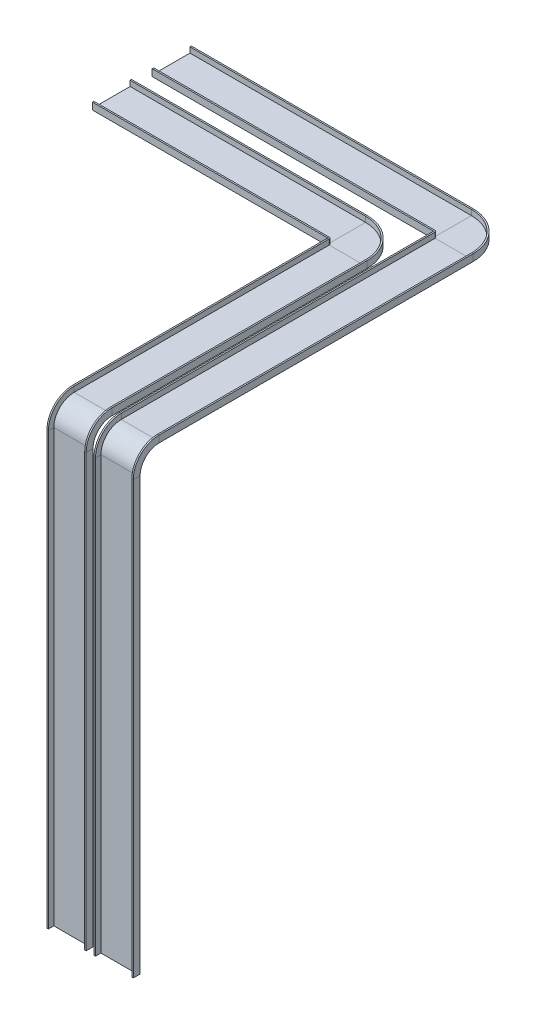
SolidWorks part; units mm, degrees
ref_plane "Alzado" through (0, 0, 0) normal (0, 0, 1) x (1, 0, 0)
ref_plane "Planta" through (0, 0, 0) normal (0, 1, 0) x (1, 0, 0)
ref_plane "Vista lateral" through (0, 0, 0) normal (1, 0, 0) x (0, 0, -1)
sketch "Croquis1" plane through (0, 0, 0) normal (0, 1, 0) x (1, 0, 0)
  line L0 (-465, 0) -> (-465, 55)
  line L1 (0, 0) -> (15, 0)
  line L2 (0, 0) -> (0, 70)
  line L3 (0, 70) -> (400, 70)
  line L4 (400, 0) -> (400, 70)
  line L5 (-80, 0) -> (-95, 0)
  line L6 (-80, 0) -> (-80, 70)
  line L7 (-80, 70) -> (-480, 70)
  line L8 (-480, 0) -> (-480, 70)
  line L9 (-465, 55) -> (-95, 55)
  line L10 (-95, 55) -> (-95, 0)
  line L11 (15, 0) -> (15, 55)
  line L12 (15, 55) -> (385, 55)
  line L13 (385, 55) -> (385, 0)
  line L14 (-465, 0) -> (-480, 0)
  line L15 (385, 0) -> (400, 0)
  dimension "D1" = 400
  dimension "D2" = 400
  dimension "D3" = 70
  dimension "D4" = 70
  dimension "D5" = 80
  dimension "D6" = 15
  dimension "D7" = 15
  dimension "D8" = 15
  dimension "D9" = 15
  dimension "D10" = 15
  dimension "D11" = 15
extrude "Saliente-Extruir1" add sketch "Croquis1" along normal blind 1000
sketch3d "Croquis3D1"
  line L0 (-280, 1000, -70) -> (-280, 1000, -55) construction
  line L1 (-80, 1000, -70) -> (-480, 1000, -70) construction
  line L2 (-465, 1000, -55) -> (-95, 1000, -55) construction
  line L3 (-280, 1000, -62.5) -> (-280, 4400, -62.5)
  line L4 (-280, 4600, -262.5) -> (-280, 4600, -2862.5)
  line L5 (-480, 4600, -3062.5) -> (-2880, 4600, -3062.5)
  arc A0 (-280, 4600, -2862.5) -> (-480, 4600, -3062.5) centre (-480, 4600, -2862.5) ccw
  arc A1 (-280, 4400, -62.5) -> (-280, 4600, -262.5) centre (-280, 4400, -262.5) ccw
  point P12 (-280, 4600, -3062.5)
  point P13 (-480, 4800, -2862.5)
  point P16 (-280, 4600, -62.5)
  point P17 (-480, 4400, -262.5)
  dimension "D4" = 200
  dimension "D1" = 3600
  dimension "D2" = 3000
  dimension "D3" = 2600
sketch "Croquis3" plane through (0, 1000, 0) normal (0, 1, 0) x (1, 0, 0)
  line L0 (-465, 0) -> (-465, 55)
  line L1 (-465, 55) -> (-95, 55)
  line L2 (-95, 55) -> (-95, 0)
  line L3 (-95, 0) -> (-80, 0)
  line L4 (-80, 0) -> (-80, 70)
  line L5 (-80, 70) -> (-480, 70)
  line L6 (-480, 70) -> (-480, 0)
  line L7 (-480, 0) -> (-465, 0)
sweep "Barrer1" add profiles "Croquis3" path "Croquis3D1"
sketch3d "Croquis3D2"
  line L0 (200, 1000, -70) -> (200, 1000, -55) construction
  line L1 (400, 1000, -70) -> (0, 1000, -70) construction
  line L2 (15, 1000, -55) -> (385, 1000, -55) construction
  line L3 (200, 1000, -62.5) -> (200, 4400, -62.5)
  line L4 (200, 4600, -262.5) -> (200, 4600, -3462.5)
  line L5 (0, 4600, -3662.5) -> (-2870, 4600, -3662.5)
  arc A0 (200, 4600, -3462.5) -> (0, 4600, -3662.5) centre (0, 4600, -3462.5) ccw
  arc A1 (200, 4400, -62.5) -> (200, 4600, -262.5) centre (200, 4400, -262.5) ccw
  point P12 (200, 4600, -3662.5)
  point P13 (0, 4800, -3462.5)
  point P16 (200, 4600, -62.5)
  point P17 (0, 4400, -262.5)
  dimension "D4" = 200
  dimension "D1" = 3600
  dimension "D2" = 3600
  dimension "D3" = 3070
sketch "Croquis4" plane through (0, 1000, 0) normal (0, 1, 0) x (1, 0, 0)
  line L0 (15, 0) -> (15, 55)
  line L1 (15, 55) -> (385, 55)
  line L2 (385, 55) -> (385, 0)
  line L3 (385, 0) -> (400, 0)
  line L4 (400, 0) -> (400, 70)
  line L5 (400, 70) -> (0, 70)
  line L6 (0, 70) -> (0, 0)
  line L7 (0, 0) -> (15, 0)
sweep "Barrer2" add profiles "Croquis4" path "Croquis3D2"
